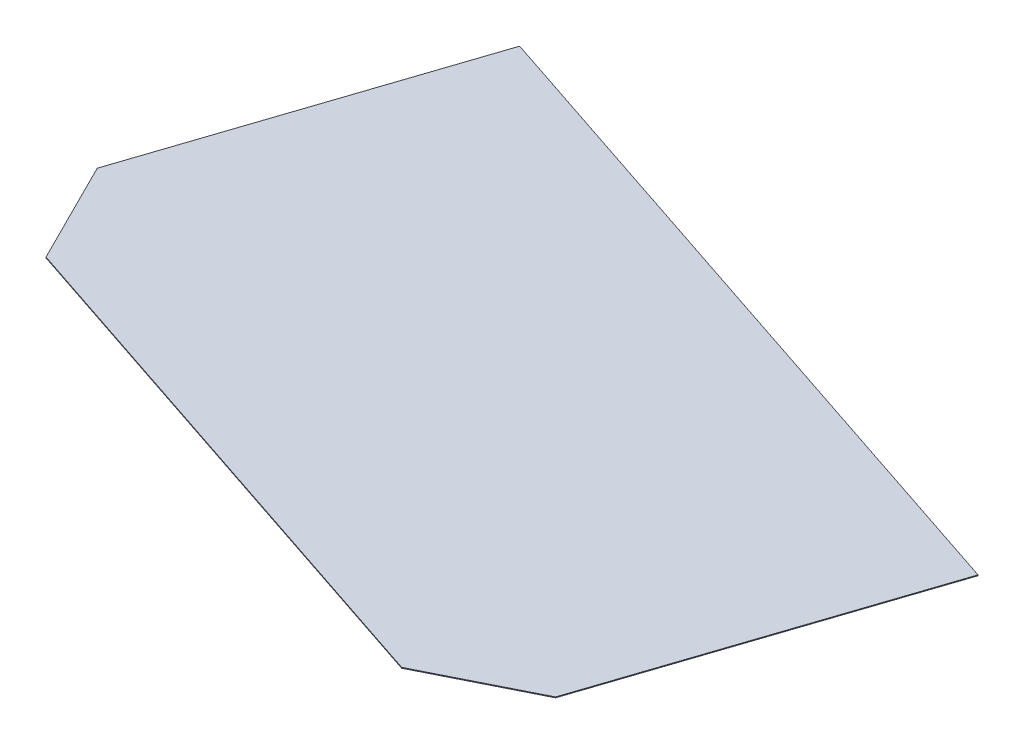
SolidWorks part; units mm, degrees
material "Glass"
ref_plane "Front Plane" through (0, 0, 0) normal (0, 0, 1) x (1, 0, 0)
ref_plane "Top Plane" through (0, 0, 0) normal (0, 1, 0) x (1, 0, 0)
ref_plane "Right Plane" through (0, 0, 0) normal (1, 0, 0) x (0, 0, -1)
sketch "Sketch1" plane through (0, 0, 0) normal (0, 1, 0) x (1, 0, 0)
  line L6 (108.2641, -39.2636) -> (42.891, -17.502)
  line L7 (42.891, -17.502) -> (32.8525, -47.6582)
  line L8 (32.8525, -47.6582) -> (37.737, -57.4174)
  line L9 (37.737, -57.4174) -> (88.4664, -74.3043)
  line L10 (88.4664, -74.3043) -> (98.2256, -69.4198)
  line L11 (98.2256, -69.4198) -> (108.2641, -39.2636)
  line L12 (108.2641, -39.2636) -> (42.891, -17.502)
  line L13 (42.891, -17.502) -> (32.8525, -47.6582)
  line L14 (32.8525, -47.6582) -> (37.737, -57.4174)
  line L15 (37.737, -57.4174) -> (88.4664, -74.3043)
  line L16 (88.4664, -74.3043) -> (98.2256, -69.4198)
  line L17 (98.2256, -69.4198) -> (108.2641, -39.2636)
  dimension "D1" = 0
extrude "Coverglass" add sketch "Sketch1" along normal mid plane 0.0762
